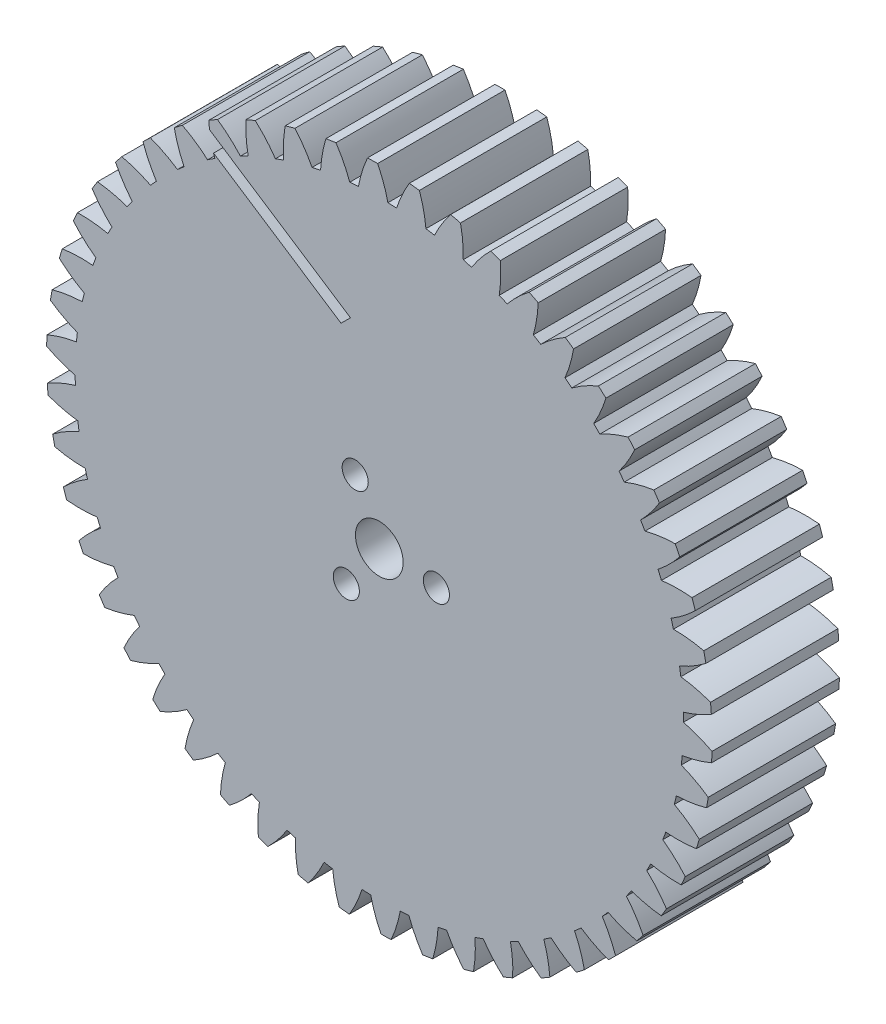
SolidWorks part; units mm, degrees
ref_plane "Front Plane" through (0, 0, 0) normal (0, 0, 1) x (1, 0, 0)
ref_plane "Top Plane" through (0, 0, 0) normal (0, 1, 0) x (1, 0, 0)
ref_plane "Right Plane" through (0, 0, 0) normal (1, 0, 0) x (0, 0, -1)
sketch "Sketch1" plane through (0, 0, 0) normal (0, 0, 1) x (1, 0, 0)
  circle A0 centre (0, 0) radius 52.3715
extrude "Boss-Extrude1" add sketch "Sketch1" along normal blind 10
extrude "Cut-Extrude1" cut sketch "Sketch2" against normal through all
sketch "Sketch2" plane through (-27.9652, -165.9867, 67.9694) normal (0, 0, 1) x (1, 0, 0)
  circle A200 centre (27.9652, 165.9867) radius 130.5991
  arc A600 (44.796, 182.9215) -> (45.7553, 185.1213) centre (36.0583, 188.041) ccw
  arc A601 (45.7553, 185.1213) -> (45.1635, 185.6549) centre (27.9652, 165.9867) ccw
  arc A602 (45.1635, 185.6549) -> (43.0744, 184.4739) centre (49.0675, 176.3106) ccw
  arc A603 (43.0744, 184.4739) -> (42.5408, 184.8975) centre (27.9652, 165.9867) ccw
  arc A604 (42.5408, 184.8975) -> (43.2168, 187.2001) centre (33.2304, 188.8814) ccw
  arc A605 (43.2168, 187.2001) -> (42.5628, 187.6553) centre (27.9652, 165.9867) ccw
  arc A606 (42.5628, 187.6553) -> (40.6382, 186.2218) centre (47.6071, 178.874) ccw
  arc A607 (40.6382, 186.2218) -> (40.0557, 186.5751) centre (27.9652, 165.9867) ccw
  arc A608 (40.0557, 186.5751) -> (40.4378, 188.9444) centre (30.3194, 189.3608) ccw
  arc A609 (40.4378, 188.9444) -> (39.7319, 189.314) centre (27.9652, 165.9867) ccw
  arc A610 (39.7319, 189.314) -> (38.0021, 187.6506) centre (45.8371, 181.2342) ccw
  arc A611 (38.0021, 187.6506) -> (37.38, 187.9281) centre (27.9652, 165.9867) ccw
  arc A612 (37.38, 187.9281) -> (37.4621, 190.3266) centre (27.3713, 189.4715) ccw
  arc A613 (37.4621, 190.3266) -> (36.7155, 190.6049) centre (27.9652, 165.9867) ccw
  arc A614 (36.7155, 190.6049) -> (35.2078, 188.7377) centre (43.7851, 183.3539) ccw
  arc A615 (35.2078, 188.7377) -> (34.5557, 188.9351) centre (27.9652, 165.9867) ccw
  arc A616 (34.5557, 188.9351) -> (34.3366, 191.3249) centre (24.4325, 189.2119) ccw
  arc A617 (34.3366, 191.3249) -> (33.561, 191.5074) centre (27.9652, 165.9867) ccw
  arc A618 (33.561, 191.5074) -> (32.2992, 189.4661) centre (41.4837, 185.1997) ccw
  arc A619 (32.2992, 189.4661) -> (31.6276, 189.5802) centre (27.9652, 165.9867) ccw
  arc A620 (31.6276, 189.5802) -> (31.1107, 191.9237) centre (21.5495, 188.586) ccw
  arc A621 (31.1107, 191.9237) -> (30.3183, 192.0075) centre (27.9652, 165.9867) ccw
  arc A622 (30.3183, 192.0075) -> (29.3223, 189.8241) centre (38.9691, 186.7425) ccw
  arc A623 (29.3223, 189.8241) -> (28.6416, 189.8531) centre (27.9652, 165.9867) ccw
  arc A624 (28.6416, 189.8531) -> (27.8351, 192.1134) centre (18.7676, 187.6037) ccw
  arc A625 (27.8351, 192.1134) -> (27.0384, 192.0973) centre (27.9652, 165.9867) ccw
  arc A626 (27.0384, 192.0973) -> (26.324, 189.8062) centre (36.2809, 187.958) ccw
  arc A627 (26.324, 189.8062) -> (25.6451, 189.7497) centre (27.9652, 165.9867) ccw
  arc A628 (25.6451, 189.7497) -> (24.5616, 191.8911) centre (16.1308, 186.2805) ccw
  arc A629 (24.5616, 191.8911) -> (23.7732, 191.7752) centre (27.9652, 165.9867) ccw
  arc A630 (23.7732, 191.7752) -> (23.3515, 189.4127) centre (33.4616, 188.827) ccw
  arc A631 (23.3515, 189.4127) -> (22.6851, 189.2715) centre (27.9652, 165.9867) ccw
  arc A632 (22.6851, 189.2715) -> (21.3417, 191.2602) centre (13.6807, 184.6372) ccw
  arc A633 (21.3417, 191.2602) -> (20.5741, 191.0465) centre (27.9652, 165.9867) ccw
  arc A634 (20.5741, 191.0465) -> (20.4519, 188.6497) centre (30.5556, 189.3358) ccw
  arc A635 (20.4519, 188.6497) -> (19.8083, 188.4262) centre (27.9652, 165.9867) ccw
  arc A636 (19.8083, 188.4262) -> (18.2264, 190.2308) centre (11.4558, 182.6998) ccw
  arc A637 (18.2264, 190.2308) -> (17.4916, 189.9225) centre (27.9652, 165.9867) ccw
  arc A638 (17.4916, 189.9225) -> (17.6707, 187.5294) centre (27.6088, 189.4763) ccw
  arc A639 (17.6707, 187.5294) -> (17.0602, 187.2269) centre (27.9652, 165.9867) ccw
  arc A640 (17.0602, 187.2269) -> (15.2646, 188.819) centre (9.4913, 180.4988) ccw
  arc A641 (15.2646, 188.819) -> (14.5742, 188.4211) centre (27.9652, 165.9867) ccw
  arc A642 (14.5742, 188.4211) -> (15.0518, 186.0692) centre (24.6675, 189.2464) ccw
  arc A643 (15.0518, 186.0692) -> (14.4841, 185.6926) centre (27.9652, 165.9867) ccw
  arc A644 (14.4841, 185.6926) -> (12.5031, 187.0472) centre (7.8181, 178.069) ccw
  arc A645 (12.5031, 187.0472) -> (11.868, 186.5659) centre (27.9652, 165.9867) ccw
  arc A646 (11.868, 186.5659) -> (12.6367, 184.2924) centre (21.7783, 188.6497) ccw
  arc A647 (12.6367, 184.2924) -> (12.1206, 183.8476) centre (27.9652, 165.9867) ccw
  arc A648 (12.1206, 183.8476) -> (9.9854, 184.9432) centre (6.4626, 175.4486) ccw
  arc A649 (9.9854, 184.9432) -> (9.4157, 184.3861) centre (27.9652, 165.9867) ccw
  arc A650 (9.4157, 184.3861) -> (10.4632, 182.2269) centre (18.9867, 187.6956) ccw
  arc A651 (10.4632, 182.2269) -> (10.007, 181.7209) centre (27.9652, 165.9867) ccw
  arc A652 (10.007, 181.7209) -> (7.7513, 182.5402) centre (5.4463, 172.679) ccw
  arc A653 (7.7513, 182.5402) -> (7.2559, 181.9161) centre (27.9652, 165.9867) ccw
  arc A654 (7.2559, 181.9161) -> (8.5658, 179.9053) centre (16.3366, 186.3991) ccw
  arc A655 (8.5658, 179.9053) -> (8.1766, 179.3461) centre (27.9652, 165.9867) ccw
  arc A656 (8.1766, 179.3461) -> (5.836, 179.8762) centre (4.7851, 169.8039) ccw
  arc A657 (5.836, 179.8762) -> (5.4228, 179.195) centre (27.9652, 165.9867) ccw
  arc A658 (5.4228, 179.195) -> (6.9743, 177.3641) centre (13.87, 184.7807) ccw
  arc A659 (6.9743, 177.3641) -> (6.6582, 176.7606) centre (27.9652, 165.9867) ccw
  arc A660 (6.6582, 176.7606) -> (4.2697, 176.9932) centre (4.4895, 166.8686) ccw
  arc A661 (4.2697, 176.9932) -> (3.9451, 176.2655) centre (27.9652, 165.9867) ccw
  arc A662 (3.9451, 176.2655) -> (5.7139, 174.6435) centre (11.6256, 182.8659) ccw
  arc A663 (5.7139, 174.6435) -> (5.4759, 174.0052) centre (27.9652, 165.9867) ccw
  arc A664 (5.4759, 174.0052) -> (3.0771, 173.9365) centre (4.564, 163.9193) ccw
  arc A665 (3.0771, 173.9365) -> (2.8462, 173.1739) centre (27.9652, 165.9867) ccw
  arc A666 (2.8462, 173.1739) -> (4.8043, 171.7864) centre (9.6389, 180.6849) ccw
  arc A667 (4.8043, 171.7864) -> (4.6483, 171.1233) centre (27.9652, 165.9867) ccw
  arc A668 (4.6483, 171.1233) -> (2.2769, 170.7545) centre (5.0077, 161.0027) ccw
  arc A669 (2.2769, 170.7545) -> (2.1435, 169.969) centre (27.9652, 165.9867) ccw
  arc A670 (2.1435, 169.969) -> (4.2601, 168.8379) centre (7.9413, 178.2721) ccw
  arc A671 (4.2601, 168.8379) -> (4.1884, 168.1604) centre (27.9652, 165.9867) ccw
  arc A672 (4.1884, 168.1604) -> (1.8819, 167.4974) centre (5.8134, 158.1646) ccw
  arc A673 (1.8819, 167.4974) -> (1.848, 166.7013) centre (27.9652, 165.9867) ccw
  arc A674 (1.848, 166.7013) -> (4.0896, 165.8444) centre (6.5594, 175.6656) ccw
  arc A675 (4.0896, 165.8444) -> (4.1034, 165.1632) centre (27.9652, 165.9867) ccw
  arc A676 (4.1034, 165.1632) -> (1.8983, 164.2163) centre (6.9684, 155.4499) ccw
  arc A677 (1.8983, 164.2163) -> (1.9644, 163.4223) centre (27.9652, 165.9867) ccw
  arc A678 (1.9644, 163.4223) -> (4.2957, 162.8531) centre (5.5151, 172.9064) ccw
  arc A679 (4.2957, 162.8531) -> (4.3948, 162.179) centre (27.9652, 165.9867) ccw
  arc A680 (4.3948, 162.179) -> (2.3257, 160.9632) centre (8.4546, 152.9014) ccw
  arc A681 (2.3257, 160.9632) -> (2.4908, 160.1837) centre (27.9652, 165.9867) ccw
  arc A682 (2.4908, 160.1837) -> (4.8751, 159.9112) centre (4.8249, 170.0381) ccw
  arc A683 (4.8751, 159.9112) -> (5.0579, 159.2549) centre (27.9652, 165.9867) ccw
  arc A684 (5.0579, 159.2549) -> (3.1575, 157.7894) centre (10.2485, 150.5593) ccw
  arc A685 (3.1575, 157.7894) -> (3.419, 157.0367) centre (27.9652, 165.9867) ccw
  arc A686 (3.419, 157.0367) -> (5.8187, 157.0652) centre (4.4996, 167.1059) ccw
  arc A687 (5.8187, 157.0652) -> (6.0822, 156.4369) centre (27.9652, 165.9867) ccw
  arc A688 (6.0822, 156.4369) -> (4.3805, 154.7448) centre (12.3217, 148.4604) ccw
  arc A689 (4.3805, 154.7448) -> (4.7343, 154.0308) centre (27.9652, 165.9867) ccw
  arc A690 (4.7343, 154.0308) -> (7.1115, 154.3598) centre (4.5443, 164.156) ccw
  arc A691 (7.1115, 154.3598) -> (7.4517, 153.7696) centre (27.9652, 165.9867) ccw
  arc A692 (7.4517, 153.7696) -> (5.9755, 151.8775) centre (14.6417, 146.638) ccw
  arc A693 (5.9755, 151.8775) -> (6.4159, 151.2135) centre (27.9652, 165.9867) ccw
  arc A694 (6.4159, 151.2135) -> (8.7331, 151.8378) centre (4.9585, 161.2351) ccw
  arc A695 (8.7331, 151.8378) -> (9.1446, 151.2949) centre (27.9652, 165.9867) ccw
  arc A696 (9.1446, 151.2949) -> (7.9172, 149.2327) centre (17.1718, 145.1207) ccw
  arc A697 (7.9172, 149.2327) -> (8.4374, 148.6291) centre (27.9652, 165.9867) ccw
  arc A698 (8.4374, 148.6291) -> (10.6581, 149.539) centre (5.7354, 158.389) ccw
  arc A699 (10.6581, 149.539) -> (11.1344, 149.0519) centre (27.9652, 165.9867) ccw
  arc A700 (11.1344, 149.0519) -> (10.1751, 146.8521) centre (19.8721, 143.9324) ccw
  arc A701 (10.1751, 146.8521) -> (10.7669, 146.3185) centre (27.9652, 165.9867) ccw
  arc A702 (10.7669, 146.3185) -> (12.856, 147.4995) centre (6.8629, 155.6628) ccw
  arc A703 (12.856, 147.4995) -> (13.3896, 147.076) centre (27.9652, 165.9867) ccw
  arc A704 (13.3896, 147.076) -> (12.7136, 144.7733) centre (22.7001, 143.092) ccw
  arc A705 (12.7136, 144.7733) -> (13.3676, 144.3181) centre (27.9652, 165.9867) ccw
  arc A706 (13.3676, 144.3181) -> (15.2922, 145.7516) centre (8.3233, 153.0994) ccw
  arc A707 (15.2922, 145.7516) -> (15.8747, 145.3983) centre (27.9652, 165.9867) ccw
  arc A708 (15.8747, 145.3983) -> (15.4926, 143.029) centre (25.6111, 142.6127) ccw
  arc A709 (15.4926, 143.029) -> (16.1985, 142.6594) centre (27.9652, 165.9867) ccw
  arc A710 (16.1985, 142.6594) -> (17.9283, 144.3228) centre (10.0934, 150.7392) ccw
  arc A711 (17.9283, 144.3228) -> (18.5505, 144.0453) centre (27.9652, 165.9867) ccw
  arc A712 (18.5505, 144.0453) -> (18.4683, 141.6468) centre (28.5592, 142.5019) ccw
  arc A713 (18.4683, 141.6468) -> (19.215, 141.3686) centre (27.9652, 165.9867) ccw
  arc A714 (19.215, 141.3686) -> (20.7226, 143.2357) centre (12.1453, 148.6195) ccw
  arc A715 (20.7226, 143.2357) -> (21.3747, 143.0383) centre (27.9652, 165.9867) ccw
  arc A716 (21.3747, 143.0383) -> (21.5938, 140.6485) centre (31.4979, 142.7615) ccw
  arc A717 (21.5938, 140.6485) -> (22.3694, 140.466) centre (27.9652, 165.9867) ccw
  arc A718 (22.3694, 140.466) -> (23.6312, 142.5074) centre (14.4467, 146.7737) ccw
  arc A719 (23.6312, 142.5074) -> (24.3029, 142.3933) centre (27.9652, 165.9867) ccw
  arc A720 (24.3029, 142.3933) -> (24.8198, 140.0497) centre (34.3809, 143.3874) ccw
  arc A721 (24.8198, 140.0497) -> (25.6121, 139.9659) centre (27.9652, 165.9867) ccw
  arc A722 (25.6121, 139.9659) -> (26.6081, 142.1493) centre (16.9614, 145.2309) ccw
  arc A723 (26.6081, 142.1493) -> (27.2888, 142.1203) centre (27.9652, 165.9867) ccw
  arc A724 (27.2888, 142.1203) -> (28.0953, 139.86) centre (37.1628, 144.3697) ccw
  arc A725 (28.0953, 139.86) -> (28.892, 139.8762) centre (27.9652, 165.9867) ccw
  arc A726 (28.892, 139.8762) -> (29.6065, 142.1672) centre (19.6495, 144.0154) ccw
  arc A727 (29.6065, 142.1672) -> (30.2854, 142.2237) centre (27.9652, 165.9867) ccw
  arc A728 (30.2854, 142.2237) -> (31.3689, 140.0824) centre (39.7996, 145.693) ccw
  arc A729 (31.3689, 140.0824) -> (32.1572, 140.1982) centre (27.9652, 165.9867) ccw
  arc A730 (32.1572, 140.1982) -> (32.5789, 142.5607) centre (22.4688, 143.1464) ccw
  arc A731 (32.5789, 142.5607) -> (33.2454, 142.7019) centre (27.9652, 165.9867) ccw
  arc A732 (33.2454, 142.7019) -> (34.5887, 140.7132) centre (42.2498, 147.3362) ccw
  arc A733 (34.5887, 140.7132) -> (35.3563, 140.9269) centre (27.9652, 165.9867) ccw
  arc A734 (35.3563, 140.9269) -> (35.4786, 143.3237) centre (25.3748, 142.6377) ccw
  arc A735 (35.4786, 143.3237) -> (36.1221, 143.5473) centre (27.9652, 165.9867) ccw
  arc A736 (36.1221, 143.5473) -> (37.7041, 141.7426) centre (44.4746, 149.2736) ccw
  arc A737 (37.7041, 141.7426) -> (38.4388, 142.0509) centre (27.9652, 165.9867) ccw
  arc A738 (38.4388, 142.0509) -> (38.2598, 144.4441) centre (28.3217, 142.4971) ccw
  arc A739 (38.2598, 144.4441) -> (38.8702, 144.7465) centre (27.9652, 165.9867) ccw
  arc A740 (38.8702, 144.7465) -> (40.6659, 143.1544) centre (46.4392, 151.4746) ccw
  arc A741 (40.6659, 143.1544) -> (41.3562, 143.5523) centre (27.9652, 165.9867) ccw
  arc A742 (41.3562, 143.5523) -> (40.8786, 145.9042) centre (31.2629, 142.727) ccw
  arc A743 (40.8786, 145.9042) -> (41.4463, 146.2808) centre (27.9652, 165.9867) ccw
  arc A744 (41.4463, 146.2808) -> (43.4274, 144.9263) centre (48.1123, 153.9044) ccw
  arc A745 (43.4274, 144.9263) -> (44.0624, 145.4076) centre (27.9652, 165.9867) ccw
  arc A746 (44.0624, 145.4076) -> (43.2938, 147.681) centre (34.1521, 143.3237) ccw
  arc A747 (43.2938, 147.681) -> (43.8098, 148.1258) centre (27.9652, 165.9867) ccw
  arc A748 (43.8098, 148.1258) -> (45.945, 147.0303) centre (49.4678, 156.5248) ccw
  arc A749 (45.945, 147.0303) -> (46.5147, 147.5874) centre (27.9652, 165.9867) ccw
  arc A750 (46.5147, 147.5874) -> (45.4672, 149.7465) centre (36.9437, 144.2778) ccw
  arc A751 (45.4672, 149.7465) -> (45.9234, 150.2525) centre (27.9652, 165.9867) ccw
  arc A752 (45.9234, 150.2525) -> (48.1791, 149.4332) centre (50.4841, 159.2944) ccw
  arc A753 (48.1791, 149.4332) -> (48.6745, 150.0573) centre (27.9652, 165.9867) ccw
  arc A754 (48.6745, 150.0573) -> (47.3646, 152.0682) centre (39.5938, 145.5743) ccw
  arc A755 (47.3646, 152.0682) -> (47.7538, 152.6273) centre (27.9652, 165.9867) ccw
  arc A756 (47.7538, 152.6273) -> (50.0944, 152.0972) centre (51.1453, 162.1695) ccw
  arc A757 (50.0944, 152.0972) -> (50.5077, 152.7785) centre (27.9652, 165.9867) ccw
  arc A758 (50.5077, 152.7785) -> (48.9561, 154.6093) centre (42.0604, 147.1927) ccw
  arc A759 (48.9561, 154.6093) -> (49.2722, 155.2128) centre (27.9652, 165.9867) ccw
  arc A760 (49.2722, 155.2128) -> (51.6607, 154.9803) centre (51.441, 165.1049) ccw
  arc A761 (51.6607, 154.9803) -> (51.9853, 155.7079) centre (27.9652, 165.9867) ccw
  arc A762 (51.9853, 155.7079) -> (50.2166, 157.3299) centre (44.3048, 149.1075) ccw
  arc A763 (50.2166, 157.3299) -> (50.4545, 157.9683) centre (27.9652, 165.9867) ccw
  arc A764 (50.4545, 157.9683) -> (52.8534, 158.0369) centre (51.3664, 168.0541) ccw
  arc A765 (52.8534, 158.0369) -> (53.0842, 158.7995) centre (27.9652, 165.9867) ccw
  arc A766 (53.0842, 158.7995) -> (51.1261, 160.187) centre (46.2915, 151.2885) ccw
  arc A767 (51.1261, 160.187) -> (51.2821, 160.8501) centre (27.9652, 165.9867) ccw
  arc A768 (51.2821, 160.8501) -> (53.6535, 161.2189) centre (50.9227, 170.9708) ccw
  arc A769 (53.6535, 161.2189) -> (53.7869, 162.0044) centre (27.9652, 165.9867) ccw
  arc A770 (53.7869, 162.0044) -> (51.6704, 163.1356) centre (47.9891, 153.7013) ccw
  arc A771 (51.6704, 163.1356) -> (51.7421, 163.813) centre (27.9652, 165.9867) ccw
  arc A772 (51.7421, 163.813) -> (54.0485, 164.4761) centre (50.117, 173.8088) ccw
  arc A773 (54.0485, 164.4761) -> (54.0824, 165.2722) centre (27.9652, 165.9867) ccw
  arc A774 (54.0824, 165.2722) -> (51.8408, 166.1291) centre (49.371, 156.3079) ccw
  arc A775 (51.8408, 166.1291) -> (51.827, 166.8102) centre (27.9652, 165.9867) ccw
  arc A776 (51.827, 166.8102) -> (54.0322, 167.7571) centre (48.962, 176.5235) ccw
  arc A777 (54.0322, 167.7571) -> (53.9661, 168.5511) centre (27.9652, 165.9867) ccw
  arc A778 (53.9661, 168.5511) -> (51.6347, 169.1204) centre (50.4153, 159.067) ccw
  arc A779 (51.6347, 169.1204) -> (51.5356, 169.7944) centre (27.9652, 165.9867) ccw
  arc A780 (51.5356, 169.7944) -> (53.6047, 171.0102) centre (47.4758, 179.072) ccw
  arc A781 (53.6047, 171.0102) -> (53.4396, 171.7897) centre (27.9652, 165.9867) ccw
  arc A782 (53.4396, 171.7897) -> (51.0553, 172.0622) centre (51.1056, 161.9353) ccw
  arc A783 (51.0553, 172.0622) -> (50.8726, 172.7185) centre (27.9652, 165.9867) ccw
  arc A784 (50.8726, 172.7185) -> (52.7729, 174.1841) centre (45.682, 181.4141) ccw
  arc A785 (52.7729, 174.1841) -> (52.5114, 174.9367) centre (27.9652, 165.9867) ccw
  arc A786 (52.5114, 174.9367) -> (50.1118, 174.9083) centre (51.4309, 164.8675) ccw
  arc A787 (50.1118, 174.9083) -> (49.8482, 175.5365) centre (27.9652, 165.9867) ccw
  arc A788 (49.8482, 175.5365) -> (51.5499, 177.2287) centre (43.6087, 183.513) ccw
  arc A789 (51.5499, 177.2287) -> (51.1962, 177.9426) centre (27.9652, 165.9867) ccw
  arc A790 (51.1962, 177.9426) -> (48.819, 177.6136) centre (51.3861, 167.8174) ccw
  arc A791 (48.819, 177.6136) -> (48.4787, 178.2038) centre (27.9652, 165.9867) ccw
  arc A792 (48.4787, 178.2038) -> (49.955, 180.096) centre (41.2887, 185.3354) ccw
  arc A793 (49.955, 180.096) -> (49.5145, 180.7599) centre (27.9652, 165.9867) ccw
  arc A794 (49.5145, 180.7599) -> (47.1973, 180.1356) centre (50.972, 170.7384) ccw
  arc A795 (47.1973, 180.1356) -> (46.7858, 180.6785) centre (27.9652, 165.9867) ccw
  arc A796 (46.7858, 180.6785) -> (48.0132, 182.7407) centre (38.7586, 186.8527) ccw
  arc A797 (48.0132, 182.7407) -> (47.493, 183.3443) centre (27.9652, 165.9867) ccw
  arc A798 (47.493, 183.3443) -> (45.2723, 182.4344) centre (50.195, 173.5844) ccw
  arc A799 (45.2723, 182.4344) -> (44.796, 182.9215) centre (27.9652, 165.9867) ccw
hole_wizard "Ø2.05 (2.05) Diameter Hole1" positions "Sketch3" profile "Sketch4" hole size "Ø2.05" standard "ISO"
sketch "Sketch3" plane through (-27.9652, -165.9867, 75.1531) normal (0, 0, 1) x (1, 0, 0)
  circle A0 centre (27.9652, 165.9867) radius 4.5
  point P0 (32.4472, 165.5842)
  point P2 (25.3756, 162.3065)
  point P4 (26.0728, 170.0695)
sketch "Sketch4" plane through (4.482, -0.4025, 75.1531) normal (1, 0, 0) x (0, -1, 0)
  line L0 (0, 0) -> (0, 75.1531)
  line L1 (0, 75.1531) -> (1.025, 75.1531)
  line L2 (1.025, 75.1531) -> (1.025, 0)
  line L3 (1.025, 0) -> (0, 0)
  line L4 (0, -6.35) -> (0, 107.95) construction
  dimension "Thru Hole Dia." = 2.05
  dimension "Thru Hole Depth" = 75.1531
extrude "Cut-Extrude2" cut sketch "Sketch5" against normal through all
sketch "Sketch5" plane through (-27.9652, -165.9867, 75.1531) normal (0, 0, 1) x (1, 0, 0)
  circle A3 centre (27.9652, 165.9867) radius 1.873
extrude "Cut-Extrude3" cut sketch "Sketch6" against normal through all
sketch "Sketch6" plane through (-27.9652, -165.9867, 67.9694) normal (0, 0, 1) x (1, 0, 0)
  line L0 (24.9619, 179.8217) -> (25.6984, 180.5582)
  line L1 (25.6984, 180.5582) -> (13.0377, 188.8575)
  line L2 (24.9619, 179.8217) -> (12.4787, 188.0048)
  line L3 (12.4787, 188.0048) -> (13.0377, 188.8575)
